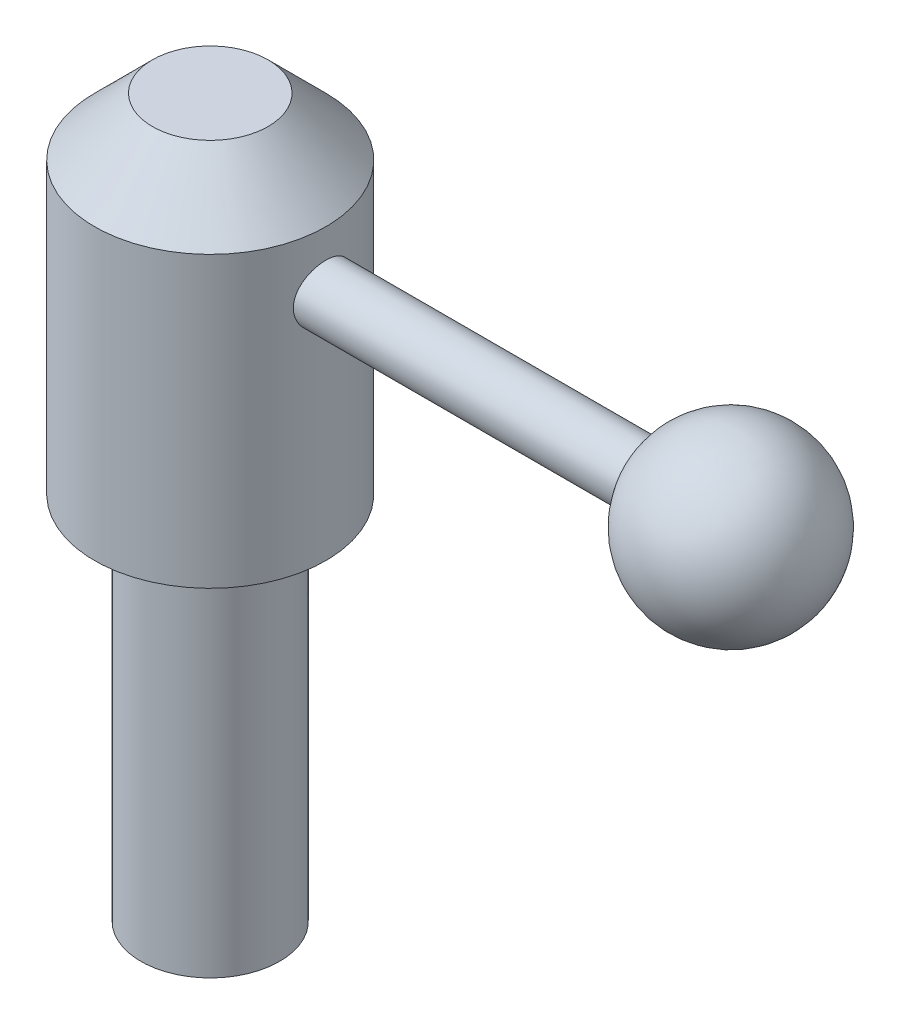
SolidWorks part; units mm, degrees
ref_plane "Front Plane" through (0, 0, 0) normal (0, 0, 1) x (1, 0, 0)
ref_plane "Top Plane" through (0, 0, 0) normal (0, 1, 0) x (1, 0, 0)
ref_plane "Right Plane" through (0, 0, 0) normal (1, 0, 0) x (0, 0, -1)
sketch "Sketch1" plane through (0, 0, 0) normal (0, 0, 1) x (1, 0, 0)
  line L0 (0, 0) -> (0, 62)
  line L1 (0, 62) -> (-10, 62)
  line L2 (-10, 62) -> (-10, 32)
  line L3 (-10, 32) -> (-6, 32)
  line L4 (-6, 32) -> (-6, 0)
  line L5 (-6, 0) -> (0, 0)
  dimension "D1" = 6
  dimension "D2" = 30
  dimension "D3" = 32
  dimension "D4" = 10
revolve "Revolve1" add sketch "Sketch1" angle 360 about L0
chamfer "Chamfer1" distance 5 angle 45 1 edges at (0, 62, -10)
sketch "Sketch2" plane through (0, 0, 0) normal (0, 0, 1) x (1, 0, 0)
  line L0 (0, 52) -> (45.8076, 52) construction
  line L1 (0, 54.5) -> (0, 52)
  line L3 (0, 54.5) -> (37.9289, 54.5)
  line L4 (-10, 32) -> (10, 32) construction
  line L5 (0, 52) -> (52.5, 52)
  arc A0 (52.5, 52) -> (37.9289, 54.5) centre (45, 52) ccw
  dimension "D1" = 15
  dimension "D2" = 20
  dimension "D3" = 45
  dimension "D4" = 2.5
revolve "Revolve2" add sketch "Sketch2" angle 360 about L0
